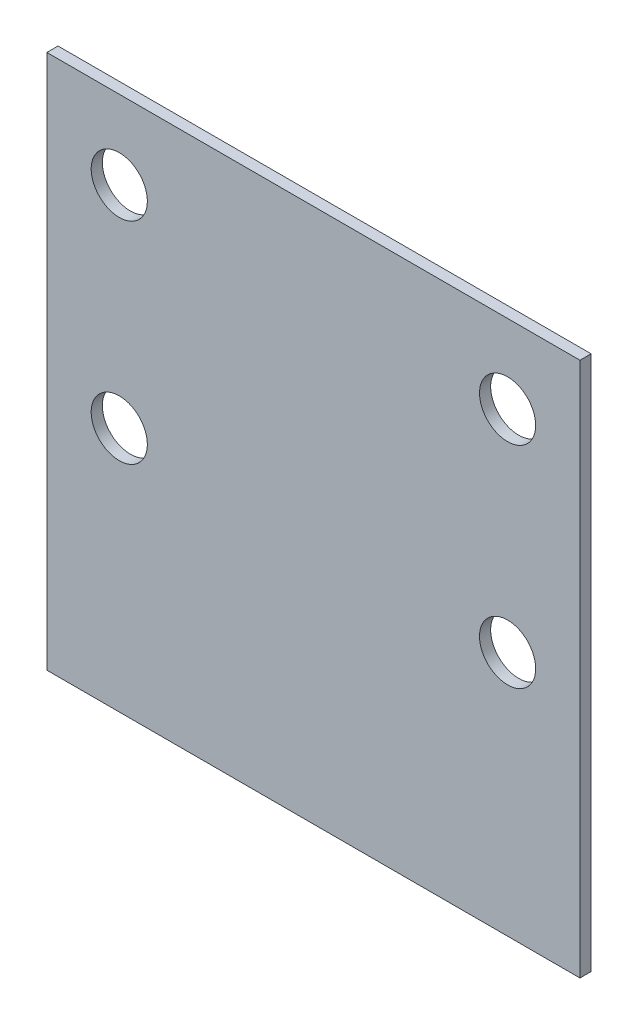
SolidWorks part; units mm, degrees
material "6061-T6 (SS)"
ref_plane "Front Plane" through (0, 0, 0) normal (0, 0, 1) x (1, 0, 0)
ref_plane "Top Plane" through (0, 0, 0) normal (0, 1, 0) x (1, 0, 0)
ref_plane "Right Plane" through (0, 0, 0) normal (1, 0, 0) x (0, 0, -1)
sketch "Sketch1" plane through (0, 0, 0) normal (0, 0, 1) x (1, 0, 0)
  line L4 (107.0164, -304.4426) -> (182.9464, -304.4426)
  line L5 (182.9464, -304.4426) -> (182.9464, -228.2426)
  line L6 (182.9464, -228.2426) -> (107.0164, -228.2426)
  line L7 (107.0164, -228.2426) -> (107.0164, -304.4426)
  line L8 (107.0164, -304.4426) -> (182.9464, -304.4426)
  line L9 (182.9464, -304.4426) -> (182.9464, -228.2426)
  line L10 (182.9464, -228.2426) -> (107.0164, -228.2426)
  line L11 (107.0164, -228.2426) -> (107.0164, -304.4426)
  circle A1 centre (117.3288, -269.4426) radius 4
  circle A2 centre (117.3288, -269.4426) radius 4
  circle A3 centre (117.3288, -239.4426) radius 4
  circle A4 centre (117.3288, -239.4426) radius 4
  circle A5 centre (172.634, -269.4426) radius 4
  circle A6 centre (172.634, -269.4426) radius 4
  circle A7 centre (172.634, -239.4426) radius 4
  circle A8 centre (172.634, -239.4426) radius 4
  dimension "D1" = 0
  dimension "D2" = 0
  dimension "D3" = 0
  dimension "D4" = 0
  dimension "D5" = 0
extrude "Boss-Extrude1" add sketch "Sketch1" along normal blind 1.5875
